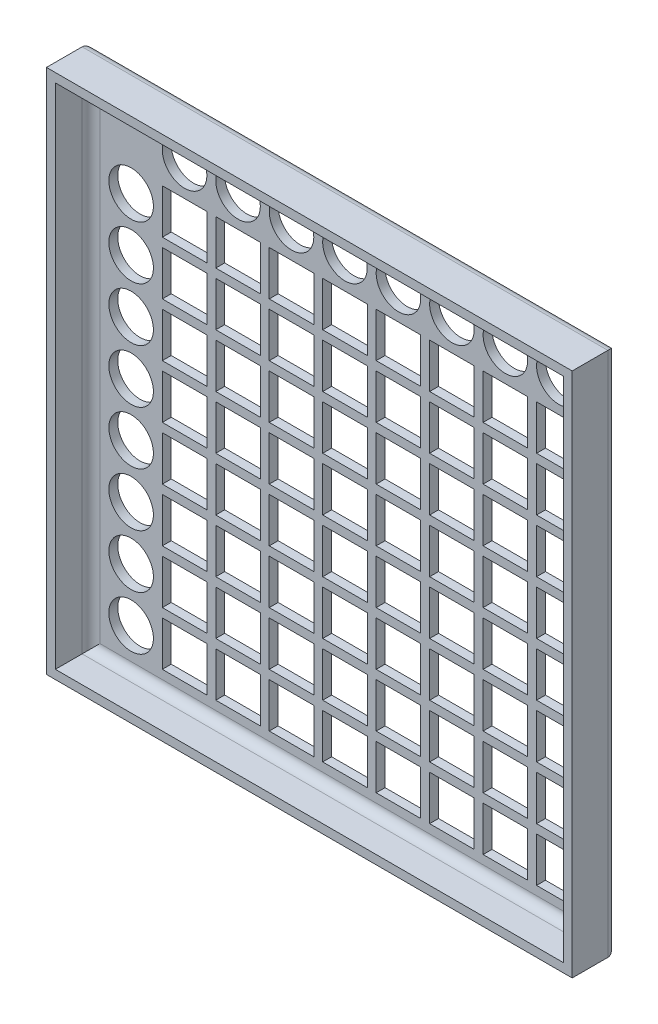
SolidWorks part; units mm, degrees
material "ABS"
ref_plane "Plano frontal" through (0, 0, 0) normal (0, 0, 1) x (1, 0, 0)
ref_plane "Plano superior" through (0, 0, 0) normal (0, 1, 0) x (1, 0, 0)
ref_plane "Plano direito" through (0, 0, 0) normal (1, 0, 0) x (0, 0, -1)
sketch "Sketch1" plane through (0, 0, 0) normal (0, 0, 1) x (1, 0, 0)
  line L0 (12, 0) -> (22, 0)
  line L1 (0, 0) -> (10, 0)
  line L2 (0, 0) -> (0, 10)
  line L3 (0, 10) -> (10, 10)
  line L4 (10, 0) -> (10, 10)
  line L5 (12, 0) -> (12, 10)
  line L6 (12, 10) -> (22, 10)
  line L7 (22, 0) -> (22, 10)
  line L8 (24, 0) -> (34, 0)
  line L9 (24, 0) -> (24, 10)
  line L10 (24, 10) -> (34, 10)
  line L11 (34, 0) -> (34, 10)
  line L12 (36, 0) -> (46, 0)
  line L13 (36, 0) -> (36, 10)
  line L14 (36, 10) -> (46, 10)
  line L15 (46, 0) -> (46, 10)
  line L16 (48, 0) -> (58, 0)
  line L17 (48, 0) -> (48, 10)
  line L18 (48, 10) -> (58, 10)
  line L19 (58, 0) -> (58, 10)
  line L20 (60, 0) -> (70, 0)
  line L21 (60, 0) -> (60, 10)
  line L22 (60, 10) -> (70, 10)
  line L23 (70, 0) -> (70, 10)
  line L24 (72, 0) -> (82, 0)
  line L25 (72, 0) -> (72, 10)
  line L26 (72, 10) -> (82, 10)
  line L27 (82, 0) -> (82, 10)
  line L28 (84, 0) -> (94, 0)
  line L29 (84, 0) -> (84, 10)
  line L30 (84, 10) -> (94, 10)
  line L31 (94, 0) -> (94, 10)
  line L32 (12, 12) -> (22, 12)
  line L33 (12, 12) -> (12, 22)
  line L34 (12, 22) -> (22, 22)
  line L35 (22, 12) -> (22, 22)
  line L36 (24, 12) -> (34, 12)
  line L37 (24, 12) -> (24, 22)
  line L38 (24, 22) -> (34, 22)
  line L39 (34, 12) -> (34, 22)
  line L40 (36, 12) -> (46, 12)
  line L41 (36, 12) -> (36, 22)
  line L42 (36, 22) -> (46, 22)
  line L43 (46, 12) -> (46, 22)
  line L44 (48, 12) -> (58, 12)
  line L45 (48, 12) -> (48, 22)
  line L46 (48, 22) -> (58, 22)
  line L47 (58, 12) -> (58, 22)
  line L48 (60, 12) -> (70, 12)
  line L49 (60, 12) -> (60, 22)
  line L50 (60, 22) -> (70, 22)
  line L51 (70, 12) -> (70, 22)
  line L52 (72, 12) -> (82, 12)
  line L53 (72, 12) -> (72, 22)
  line L54 (72, 22) -> (82, 22)
  line L55 (82, 12) -> (82, 22)
  line L56 (84, 12) -> (94, 12)
  line L57 (84, 12) -> (84, 22)
  line L58 (84, 22) -> (94, 22)
  line L59 (94, 12) -> (94, 22)
  line L60 (12, 24) -> (22, 24)
  line L61 (12, 24) -> (12, 34)
  line L62 (12, 34) -> (22, 34)
  line L63 (22, 24) -> (22, 34)
  line L64 (24, 24) -> (34, 24)
  line L65 (24, 24) -> (24, 34)
  line L66 (24, 34) -> (34, 34)
  line L67 (34, 24) -> (34, 34)
  line L68 (36, 24) -> (46, 24)
  line L69 (36, 24) -> (36, 34)
  line L70 (36, 34) -> (46, 34)
  line L71 (46, 24) -> (46, 34)
  line L72 (48, 24) -> (58, 24)
  line L73 (48, 24) -> (48, 34)
  line L74 (48, 34) -> (58, 34)
  line L75 (58, 24) -> (58, 34)
  line L76 (60, 24) -> (70, 24)
  line L77 (60, 24) -> (60, 34)
  line L78 (60, 34) -> (70, 34)
  line L79 (70, 24) -> (70, 34)
  line L80 (72, 24) -> (82, 24)
  line L81 (72, 24) -> (72, 34)
  line L82 (72, 34) -> (82, 34)
  line L83 (82, 24) -> (82, 34)
  line L84 (84, 24) -> (94, 24)
  line L85 (84, 24) -> (84, 34)
  line L86 (84, 34) -> (94, 34)
  line L87 (94, 24) -> (94, 34)
  line L88 (12, 36) -> (22, 36)
  line L89 (12, 36) -> (12, 46)
  line L90 (12, 46) -> (22, 46)
  line L91 (22, 36) -> (22, 46)
  line L92 (24, 36) -> (34, 36)
  line L93 (24, 36) -> (24, 46)
  line L94 (24, 46) -> (34, 46)
  line L95 (34, 36) -> (34, 46)
  line L96 (36, 36) -> (46, 36)
  line L97 (36, 36) -> (36, 46)
  line L98 (36, 46) -> (46, 46)
  line L99 (46, 36) -> (46, 46)
  line L100 (48, 36) -> (58, 36)
  line L101 (48, 36) -> (48, 46)
  line L102 (48, 46) -> (58, 46)
  line L103 (58, 36) -> (58, 46)
  line L104 (60, 36) -> (70, 36)
  line L105 (60, 36) -> (60, 46)
  line L106 (60, 46) -> (70, 46)
  line L107 (70, 36) -> (70, 46)
  line L108 (72, 36) -> (82, 36)
  line L109 (72, 36) -> (72, 46)
  line L110 (72, 46) -> (82, 46)
  line L111 (82, 36) -> (82, 46)
  line L112 (84, 36) -> (94, 36)
  line L113 (84, 36) -> (84, 46)
  line L114 (84, 46) -> (94, 46)
  line L115 (94, 36) -> (94, 46)
  line L116 (12, 48) -> (22, 48)
  line L117 (12, 48) -> (12, 58)
  line L118 (12, 58) -> (22, 58)
  line L119 (22, 48) -> (22, 58)
  line L120 (24, 48) -> (34, 48)
  line L121 (24, 48) -> (24, 58)
  line L122 (24, 58) -> (34, 58)
  line L123 (34, 48) -> (34, 58)
  line L124 (36, 48) -> (46, 48)
  line L125 (36, 48) -> (36, 58)
  line L126 (36, 58) -> (46, 58)
  line L127 (46, 48) -> (46, 58)
  line L128 (48, 48) -> (58, 48)
  line L129 (48, 48) -> (48, 58)
  line L130 (48, 58) -> (58, 58)
  line L131 (58, 48) -> (58, 58)
  line L132 (60, 48) -> (70, 48)
  line L133 (60, 48) -> (60, 58)
  line L134 (60, 58) -> (70, 58)
  line L135 (70, 48) -> (70, 58)
  line L136 (72, 48) -> (82, 48)
  line L137 (72, 48) -> (72, 58)
  line L138 (72, 58) -> (82, 58)
  line L139 (82, 48) -> (82, 58)
  line L140 (84, 48) -> (94, 48)
  line L141 (84, 48) -> (84, 58)
  line L142 (84, 58) -> (94, 58)
  line L143 (94, 48) -> (94, 58)
  line L144 (12, 60) -> (22, 60)
  line L145 (12, 60) -> (12, 70)
  line L146 (12, 70) -> (22, 70)
  line L147 (22, 60) -> (22, 70)
  line L148 (24, 60) -> (34, 60)
  line L149 (24, 60) -> (24, 70)
  line L150 (24, 70) -> (34, 70)
  line L151 (34, 60) -> (34, 70)
  line L152 (36, 60) -> (46, 60)
  line L153 (36, 60) -> (36, 70)
  line L154 (36, 70) -> (46, 70)
  line L155 (46, 60) -> (46, 70)
  line L156 (48, 60) -> (58, 60)
  line L157 (48, 60) -> (48, 70)
  line L158 (48, 70) -> (58, 70)
  line L159 (58, 60) -> (58, 70)
  line L160 (60, 60) -> (70, 60)
  line L161 (60, 60) -> (60, 70)
  line L162 (60, 70) -> (70, 70)
  line L163 (70, 60) -> (70, 70)
  line L164 (72, 60) -> (82, 60)
  line L165 (72, 60) -> (72, 70)
  line L166 (72, 70) -> (82, 70)
  line L167 (82, 60) -> (82, 70)
  line L168 (84, 60) -> (94, 60)
  line L169 (84, 60) -> (84, 70)
  line L170 (84, 70) -> (94, 70)
  line L171 (94, 60) -> (94, 70)
  line L172 (12, 72) -> (22, 72)
  line L173 (12, 72) -> (12, 82)
  line L174 (12, 82) -> (22, 82)
  line L175 (22, 72) -> (22, 82)
  line L176 (24, 72) -> (34, 72)
  line L177 (24, 72) -> (24, 82)
  line L178 (24, 82) -> (34, 82)
  line L179 (34, 72) -> (34, 82)
  line L180 (36, 72) -> (46, 72)
  line L181 (36, 72) -> (36, 82)
  line L182 (36, 82) -> (46, 82)
  line L183 (46, 72) -> (46, 82)
  line L184 (48, 72) -> (58, 72)
  line L185 (48, 72) -> (48, 82)
  line L186 (48, 82) -> (58, 82)
  line L187 (58, 72) -> (58, 82)
  line L188 (60, 72) -> (70, 72)
  line L189 (60, 72) -> (60, 82)
  line L190 (60, 82) -> (70, 82)
  line L191 (70, 72) -> (70, 82)
  line L192 (72, 72) -> (82, 72)
  line L193 (72, 72) -> (72, 82)
  line L194 (72, 82) -> (82, 82)
  line L195 (82, 72) -> (82, 82)
  line L196 (84, 72) -> (94, 72)
  line L197 (84, 72) -> (84, 82)
  line L198 (84, 82) -> (94, 82)
  line L199 (94, 72) -> (94, 82)
  line L200 (12, 84) -> (22, 84)
  line L201 (12, 84) -> (12, 94)
  line L202 (12, 94) -> (22, 94)
  line L203 (22, 84) -> (22, 94)
  line L204 (24, 84) -> (34, 84)
  line L205 (24, 84) -> (24, 94)
  line L206 (24, 94) -> (34, 94)
  line L207 (34, 84) -> (34, 94)
  line L208 (36, 84) -> (46, 84)
  line L209 (36, 84) -> (36, 94)
  line L210 (36, 94) -> (46, 94)
  line L211 (46, 84) -> (46, 94)
  line L212 (48, 84) -> (58, 84)
  line L213 (48, 84) -> (48, 94)
  line L214 (48, 94) -> (58, 94)
  line L215 (58, 84) -> (58, 94)
  line L216 (60, 84) -> (70, 84)
  line L217 (60, 84) -> (60, 94)
  line L218 (60, 94) -> (70, 94)
  line L219 (70, 84) -> (70, 94)
  line L220 (72, 84) -> (82, 84)
  line L221 (72, 84) -> (72, 94)
  line L222 (72, 94) -> (82, 94)
  line L223 (82, 84) -> (82, 94)
  line L224 (84, 84) -> (94, 84)
  line L225 (84, 84) -> (84, 94)
  line L226 (84, 94) -> (94, 94)
  line L227 (94, 84) -> (94, 94)
  line L228 (0, 12) -> (10, 12)
  line L229 (0, 12) -> (0, 22)
  line L230 (0, 22) -> (10, 22)
  line L231 (10, 12) -> (10, 22)
  line L232 (0, 24) -> (10, 24)
  line L233 (0, 24) -> (0, 34)
  line L234 (0, 34) -> (10, 34)
  line L235 (10, 24) -> (10, 34)
  line L236 (0, 36) -> (10, 36)
  line L237 (0, 36) -> (0, 46)
  line L238 (0, 46) -> (10, 46)
  line L239 (10, 36) -> (10, 46)
  line L240 (0, 48) -> (10, 48)
  line L241 (0, 48) -> (0, 58)
  line L242 (0, 58) -> (10, 58)
  line L243 (10, 48) -> (10, 58)
  line L244 (0, 60) -> (10, 60)
  line L245 (0, 60) -> (0, 70)
  line L246 (0, 70) -> (10, 70)
  line L247 (10, 60) -> (10, 70)
  line L248 (0, 72) -> (10, 72)
  line L249 (0, 72) -> (0, 82)
  line L250 (0, 82) -> (10, 82)
  line L251 (10, 72) -> (10, 82)
  line L252 (0, 84) -> (10, 84)
  line L253 (0, 84) -> (0, 94)
  line L254 (0, 94) -> (10, 94)
  line L255 (10, 84) -> (10, 94)
  line L256 (0, 0) -> (0, 94) construction
  line L257 (0, 0) -> (94, 0) construction
  line L258 (89, 0) -> (89, 101) construction
  line L259 (-18, 112) -> (100, 112)
  line L260 (-18, 112) -> (-18, -6)
  line L261 (-18, -6) -> (100, -6)
  line L262 (100, 112) -> (100, -6)
  line L263 (94, 5) -> (-7, 5) construction
  line L264 (-7, 5) -> (-7, 89) construction
  line L265 (89, 101) -> (5, 101) construction
  circle A0 centre (89, 101) radius 5
  circle A1 centre (77, 101) radius 5
  circle A2 centre (65, 101) radius 5
  circle A3 centre (53, 101) radius 5
  circle A4 centre (41, 101) radius 5
  circle A5 centre (29, 101) radius 5
  circle A6 centre (17, 101) radius 5
  circle A7 centre (5, 101) radius 5
  circle A8 centre (-7, 5) radius 5
  circle A9 centre (-7, 17) radius 5
  circle A10 centre (-7, 29) radius 5
  circle A11 centre (-7, 41) radius 5
  circle A12 centre (-7, 53) radius 5
  circle A13 centre (-7, 65) radius 5
  circle A14 centre (-7, 77) radius 5
  circle A15 centre (-7, 89) radius 5
  dimension "D11" = 10
  dimension "D14" = 10
  dimension "D1" = 10
  dimension "D2" = 10
  dimension "D5" = 2
  dimension "D6" = 2
  dimension "D7" = 18
  dimension "D8" = 18
  dimension "D9" = 6
  dimension "D10" = 6
  dimension "D12" = 7
  dimension "D15" = 7
  dimension "D17" = 12
  dimension "D18" = 12
  dimension "D3" = 8
  dimension "D4" = 8
  dimension "D13" = 8
  dimension "D16" = 8
extrude "Boss-Extrude2" add sketch "Sketch1" along normal blind 10
sketch "Sketch3" plane through (0, 0, 10) normal (0, 0, 1) x (1, 0, 0)
  line L0 (-18, 112) -> (-18, -6) construction
  line L1 (-16, 110) -> (98, 110)
  line L2 (-16, 110) -> (-16, -4)
  line L3 (-16, -4) -> (98, -4)
  line L4 (98, 110) -> (98, -4)
  line L5 (100, 112) -> (-18, 112) construction
  line L6 (100, -6) -> (100, 112) construction
  dimension "D1" = 2
  dimension "D2" = 2
  dimension "D3" = 2
extrude "Cut-Extrude2" cut sketch "Sketch3" against normal blind 8
fillet "Fillet1" radius 2 8 edges at (41, -6, 0) (-18, 53, 0) (41, 112, 0) (100, 53, 0) (41, 110, 2) (98, 53, 2) (41, -4, 2) (-16, 53, 2)
sketch "Sketch4" plane through (0, 0, 0) normal (0, 0, -1) x (-1, 0, 0)
  text T0 "<b>Dalle</b>\r\n<b> Pad</b>"
extrude "Cut-Extrude3" cut sketch "Sketch4" against normal mid plane 1
